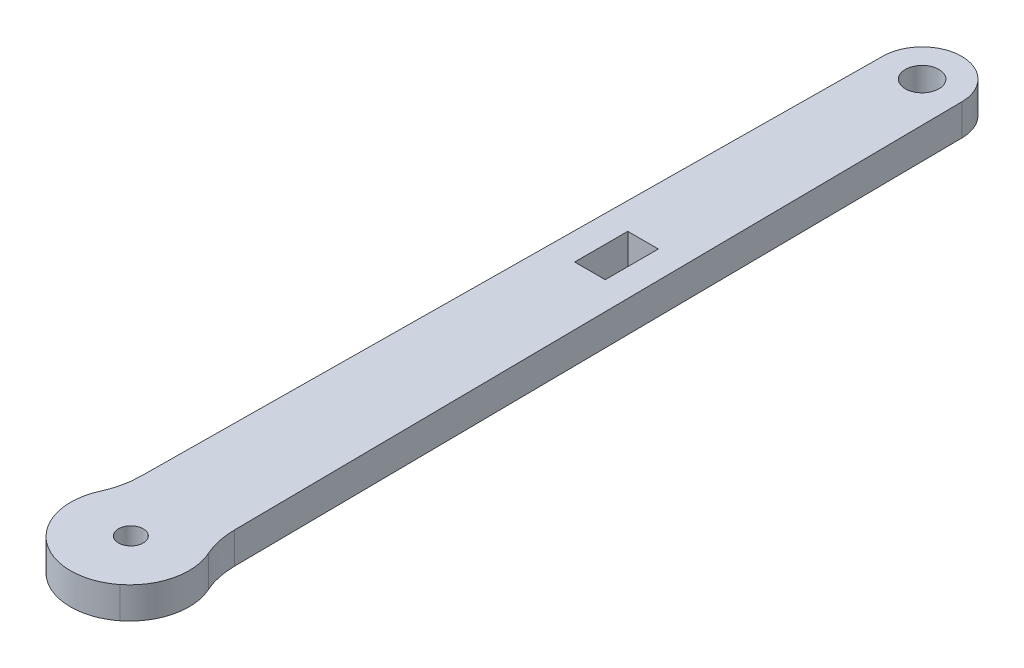
SolidWorks part; units mm, degrees
material "Acrylic (Medium-high impact)"
ref_plane "Front Plane" through (0, 0, 0) normal (0, 0, 1) x (1, 0, 0)
ref_plane "Top Plane" through (0, 0, 0) normal (0, 1, 0) x (1, 0, 0)
ref_plane "Right Plane" through (0, 0, 0) normal (1, 0, 0) x (0, 0, -1)
sketch "Sketch1" plane through (0, 0, 0) normal (0, 1, 0) x (1, 0, 0)
  line L0 (-14.7183, -42.348) -> (-11.7237, -42.3777) construction
  line L1 (-14.7107, 37.6549) -> (-11.7163, 37.6252) construction
  line L377 (-14.767, 9.4303) -> (-14.767, 4.0567)
  line L378 (-14.767, 4.0567) -> (-11.6729, 4.0567)
  line L379 (-11.6729, 4.0567) -> (-11.6729, 9.4303)
  line L380 (-11.6729, 9.4303) -> (-14.767, 9.4303)
  line L389 (-17.9415, -36.6127) -> (-17.2063, 37.6798)
  line L390 (-9.221, 37.6791) -> (-8.4992, -36.6136)
  circle A0 centre (-13.221, -42.3629) radius 1.25
  circle A1 centre (-13.2135, 37.6401) radius 1.7
  spline S178 degree 3 poles (-7.7759, -39.9655) (-6.625, -42.4844) (-7.3451, -45.4655) (-9.5183, -47.1786) knots 0 0 0 0 1 1 1 1
  spline S179 degree 3 poles (-9.5183, -47.1786) (-11.6917, -48.8917) (-14.7532, -48.8913) (-16.9263, -47.1778) knots 1 1 1 1 2 2 2 2
  spline S180 degree 3 poles (-16.9263, -47.1778) (-19.0993, -45.4644) (-19.8188, -42.4831) (-18.6674, -39.9644) knots 2 2 2 2 3 3 3 3
  spline S181 degree 3 poles (-18.6674, -39.9644) (-18.2007, -38.9434) (-17.9526, -37.7355) (-17.9415, -36.6127) knots 3 3 3 3 4 4 4 4
  spline S182 degree 3 poles (-17.2063, 37.6798) (-17.1845, 39.8735) (-15.4032, 41.6404) (-13.2133, 41.6402) knots 5 5 5 5 6 6 6 6
  spline S183 degree 3 poles (-13.2133, 41.6402) (-11.0233, 41.6399) (-9.2421, 39.8727) (-9.221, 37.6791) knots 6 6 6 6 7 7 7 7
  spline S184 degree 3 poles (-8.4992, -36.6136) (-8.4883, -37.7364) (-8.2426, -38.9443) (-7.7759, -39.9655) knots 8 8 8 8 9 9 9 9
  dimension "D1" = 2.5
  dimension "D2" = 3.4
extrude "Boss-Extrude1" add sketch "Sketch1" along normal blind 3.175
